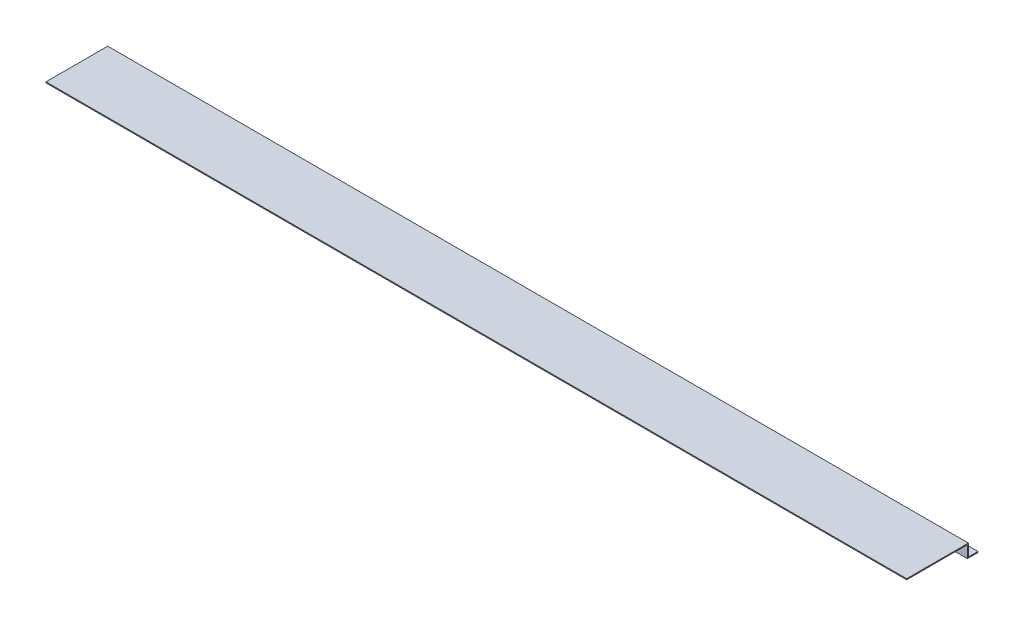
SolidWorks part; units mm, degrees
ref_plane "Front Plane" through (0, 0, 0) normal (0, 0, 1) x (1, 0, 0)
ref_plane "Top Plane" through (0, 0, 0) normal (0, 1, 0) x (1, 0, 0)
ref_plane "Right Plane" through (0, 0, 0) normal (1, 0, 0) x (0, 0, -1)
sketch "Sketch1" plane through (0, 0, 0) normal (1, 0, 0) x (0, 0, -1)
  line L8 (0, 0) -> (128, 0)
  line L9 (128, 0) -> (128, -25)
  line L10 (128, -25) -> (148, -25)
  line L11 (0, -2) -> (126, -2)
  line L12 (126, -2) -> (126, -27)
  line L13 (126, -27) -> (148, -27)
  line L14 (0, 0) -> (0, -2)
  line L15 (148, -25) -> (148, -27)
  dimension "D1" = 2
  dimension "D2" = 128
  dimension "D3" = 27
  dimension "D4" = 22
extrude "Boss-Extrude2" add sketch "Sketch1" along normal blind 1785
equation "\"door_base_double_R1_R_open_height\"= 1785"
equation "\"D1@Boss-Extrude2\"=\"door_base_double_R1_R_open_height\""
